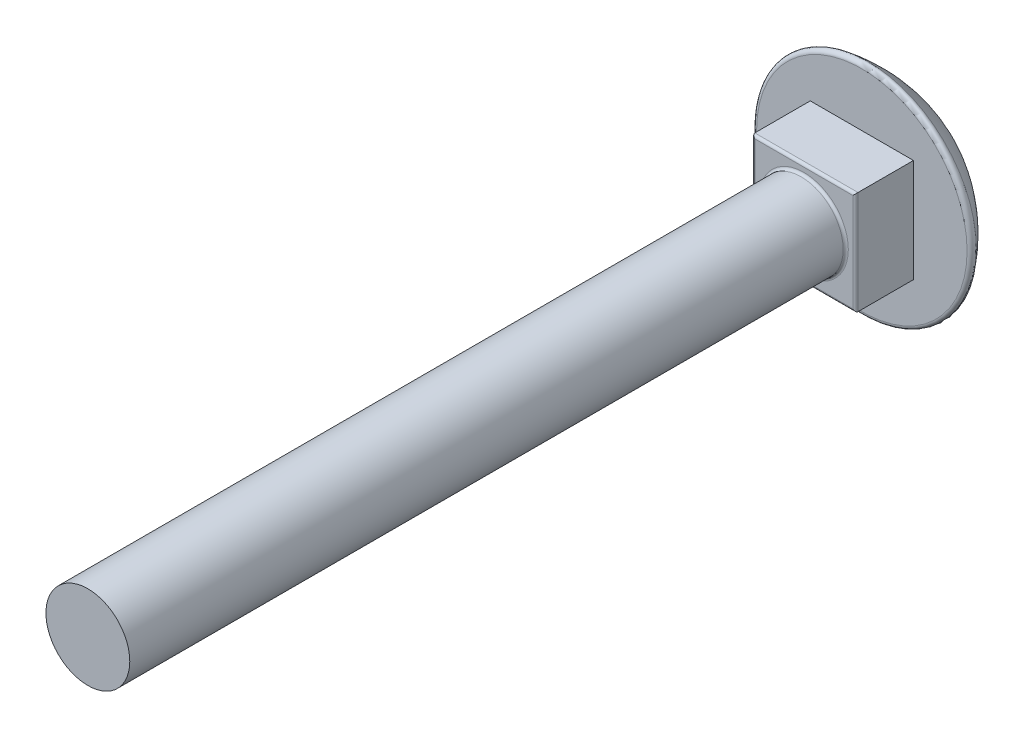
SolidWorks part; units mm, degrees
ref_plane "Front Plane" through (0, 0, 0) normal (0, 0, 1) x (1, 0, 0)
ref_plane "Top Plane" through (0, 0, 0) normal (0, 1, 0) x (1, 0, 0)
ref_plane "Right Plane" through (0, 0, 0) normal (1, 0, 0) x (0, 0, -1)
sketch "Sketch1" plane through (0, 0, 0) normal (0, 1, 0) x (1, 0, 0)
  line L0 (0, 0) -> (0, 60)
  line L1 (0, 0) -> (-3.25, 0)
  line L2 (-3.25, 0) -> (-3.25, 60)
  line L3 (0, 60) -> (5.5, 60)
  line L4 (-3.25, 60) -> (-3.25, 65)
  arc A1 (5.5, 60) -> (-3.25, 65) centre (-4.1534, 53.2627) ccw
  dimension "D1" = 60
  dimension "D2" = 3.25
  dimension "D3" = 8.75
  dimension "D4" = 5
revolve "Revolve1" add sketch "Sketch1" angle 360 about L2
sketch "Sketch2" plane through (0, 0, -60) normal (0, 0, 1) x (1, 0, 0)
  line L1 (-7.25, 4) -> (0.75, 4)
  line L2 (-7.25, 4) -> (-7.25, -4)
  line L3 (-7.25, -4) -> (0.75, -4)
  line L4 (0.75, 4) -> (0.75, -4)
  line L5 (-7.25, 4) -> (0.75, -4) construction
  line L6 (-7.25, -4) -> (0.75, 4) construction
  point P0 (-3.25, 0)
  dimension "D1" = 8
  dimension "D2" = 8
extrude "Boss-Extrude1" add sketch "Sketch2" along normal blind 4.5
fillet "Fillet3" radius 0.2 5 edges at (-3.25, -4, -55.5) (-7.25, 0, -55.5) (-3.25, 4, -55.5) (0.75, 0, -55.5) (0, 0, -55.5)
fillet "Fillet4" radius 0.3 1 edges at (5.5, 0, -60)
